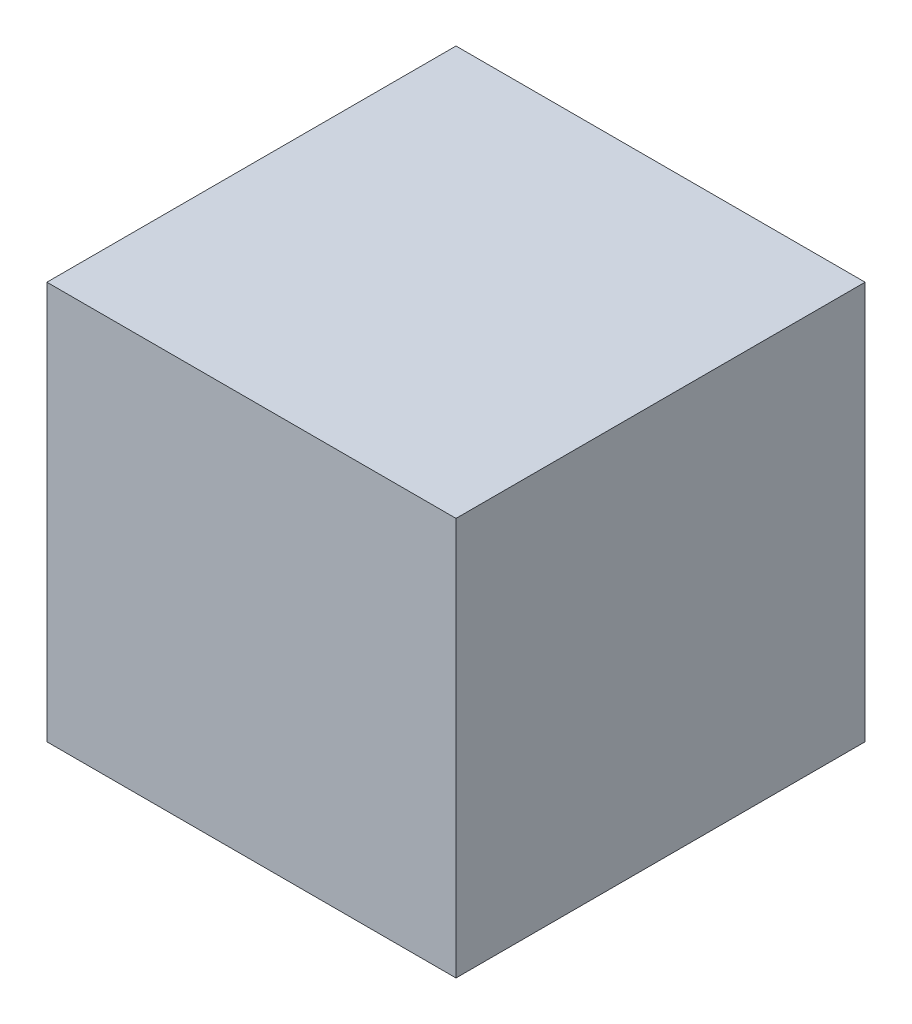
SolidWorks part; units mm, degrees
ref_plane "Front Plane" through (0, 0, 0) normal (0, 0, 1) x (1, 0, 0)
ref_plane "Top Plane" through (0, 0, 0) normal (0, 1, 0) x (1, 0, 0)
ref_plane "Right Plane" through (0, 0, 0) normal (1, 0, 0) x (0, 0, -1)
sketch "Sketch1" plane through (0, 0, 0) normal (0, 1, 0) x (1, 0, 0)
  line L1 (-469.9, -469.9) -> (469.9, -469.9)
  line L2 (-469.9, -469.9) -> (-469.9, 469.9)
  line L3 (-469.9, 469.9) -> (469.9, 469.9)
  line L4 (469.9, -469.9) -> (469.9, 469.9)
  line L5 (-469.9, -469.9) -> (469.9, 469.9) construction
  line L6 (-469.9, 469.9) -> (469.9, -469.9) construction
  point P0 (0, 0)
  dimension "D1" = 939.8
  dimension "D2" = 939.8
extrude "Boss-Extrude1" add sketch "Sketch1" along normal blind 914.4
